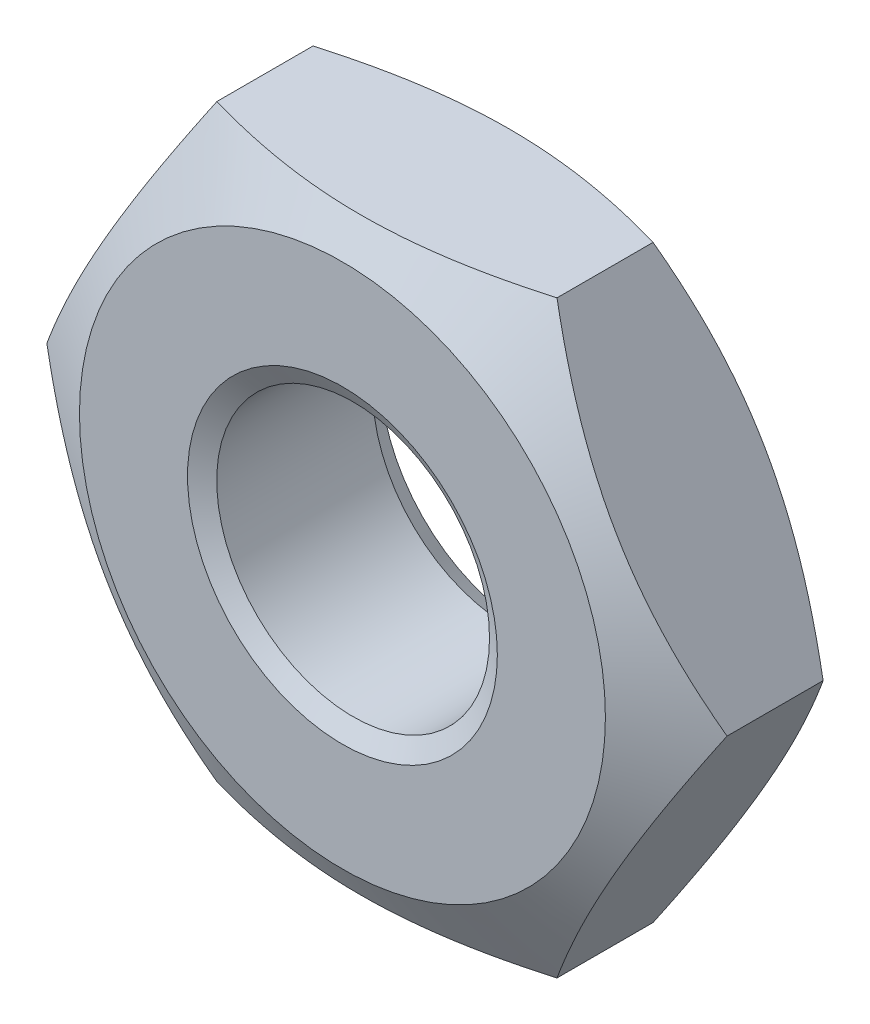
SolidWorks part; units mm, degrees
ref_plane "Front" through (0, 0, 0) normal (0, 0, 1) x (1, 0, 0)
ref_plane "Top" through (0, 0, 0) normal (0, 1, 0) x (1, 0, 0)
ref_plane "Right" through (0, 0, 0) normal (1, 0, 0) x (0, 0, -1)
sketch "Sketch1" plane through (0, 0, 0) normal (0, 0, 1) x (1, 0, 0)
  line L1 (2.0207, -3.5) -> (4.0415, 0)
  line L2 (4.0415, 0) -> (2.0207, 3.5)
  line L3 (2.0207, 3.5) -> (-2.0207, 3.5)
  line L4 (-2.0207, 3.5) -> (-4.0415, 0)
  line L5 (-4.0415, 0) -> (-2.0207, -3.5)
  line L6 (-2.0207, -3.5) -> (2.0207, -3.5)
  circle A0 centre (0, 0) radius 3.5 construction
  circle A1 centre (0, 0) radius 1.621
  dimension "D" = 3.242
  dimension "s" = 7
extrude "BaseNut" add sketch "Sketch1" against normal blind 2.2
cosmetic thread "ThreadCosmetic1" parameters "D"=4
sketch "Sketch2" plane through (0, 0, 0) normal (0, 1, 0) x (1, 0, 0)
  line L0 (-4.0415, 2.2) -> (-3.125, 2.2)
  line L2 (-3.125, 2.2) -> (-4.0415, 1.6709)
  line L3 (-4.0415, 1.6709) -> (-4.0415, 2.2)
  line L4 (0, 3.3759) -> (0, -9.8171) construction
  line L6 (-9.7712, 1.1) -> (9.8853, 1.1) construction
  line L7 (-4.0415, 0.5291) -> (-4.0415, 0)
  line L8 (-3.125, 0) -> (-4.0415, 0.5291)
  line L9 (-4.0415, 0) -> (-3.125, 0)
  dimension "dw" = 6.25
  dimension "D1" = 30
  dimension "D2" = 1.1
revolve "Double-Chamfer" cut sketch "Sketch2" angle 360 about L4
chamfer "EndChamfer" distance 0.22 angle 30 2 edges at (1.621, 0, -2.2) (1.621, 0, 0)
sketch "Sketch3" plane through (0, 0, 0) normal (0, 1, 0) x (1, 0, 0)
  line L0 (0, 6.7075) -> (0, -2.1252) construction
  line L1 (1.242, 2.1695) -> (1.621, 2.1695)
  line L2 (1.621, 2.1695) -> (1.9492, 1.98)
  line L3 (1.9492, 1.98) -> (1.621, 1.7905)
  line L4 (1.621, 1.7905) -> (1.242, 1.7905)
  line L5 (1.242, 1.7905) -> (1.242, 2.1695)
  line L6 (1.621, 1.98) -> (-1.621, 1.98) construction
  dimension "D1" = 0.379
  dimension "D2" = 3.242
revolve "Cut-Revolve10" [suppressed] cut sketch "Sketch3" angle 360 about L0
pattern_linear "LPattern10" [suppressed] count 4 spacing 0.4548 along (0, 0, 1)
equation "\"dw@Sketch2\" = \"s@Sketch1\"-0.75"
equation "\"D2@Sketch2\" = \"m@BaseNut\" / 2"
equation "\"D1@EndChamfer\" = \"m@BaseNut\" / 10"
equation "\"D2@Sketch3\" = \"D@Sketch1\""
equation "\"D1@Sketch3\" = (  \"D@ThreadCosmetic1\" - \"D@Sketch1\" )  / 2"
equation "\"D3@LPattern10\" = \"D1@Sketch3\" * 1.2"
equation "\"D1@LPattern10\" = (  \"m@BaseNut\" - \"D1@EndChamfer\" )  / \"D3@LPattern10\" "
